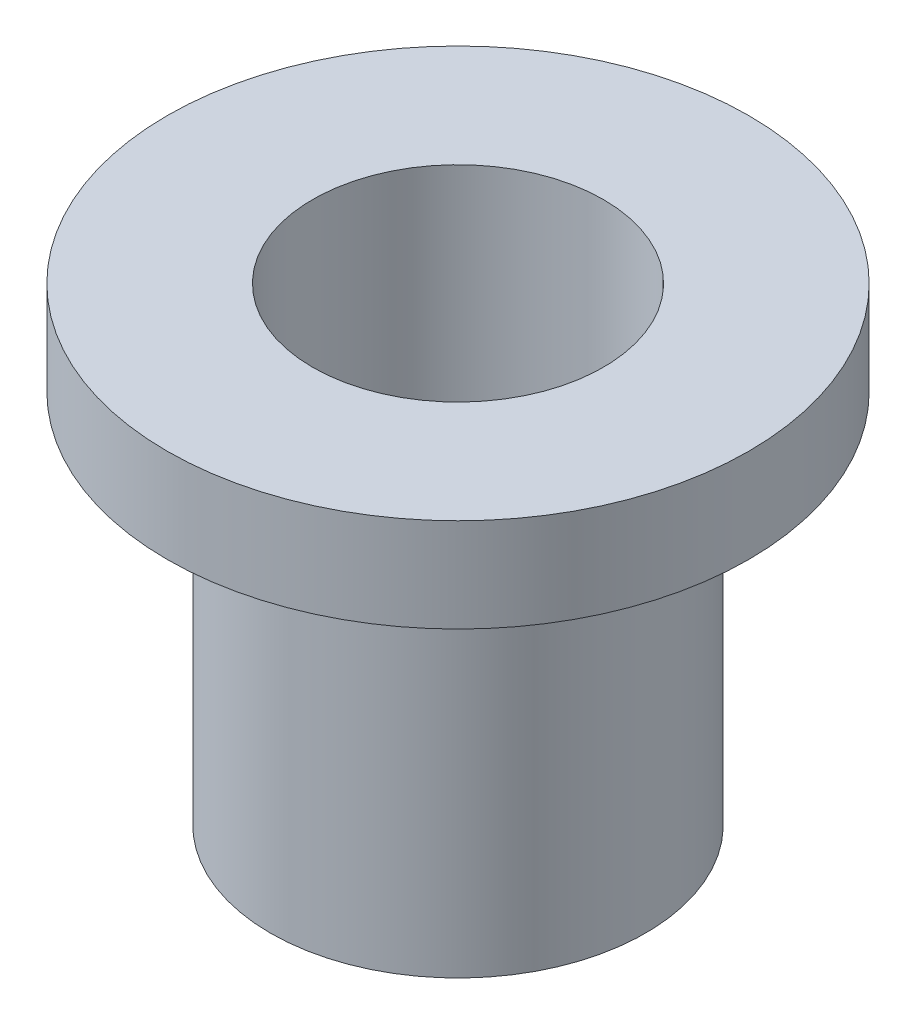
SolidWorks part; units mm, degrees
material "Nylon 101"
ref_plane "Front Plane" through (0, 0, 0) normal (0, 0, 1) x (1, 0, 0)
ref_plane "Top Plane" through (0, 0, 0) normal (0, 1, 0) x (1, 0, 0)
ref_plane "Right Plane" through (0, 0, 0) normal (1, 0, 0) x (0, 0, -1)
sketch "Sketch1" plane through (0, 0, 0) normal (1, 0, 0) x (0, 0, -1)
  line L0 (0, 8.7617) -> (0, -8.7617) construction
  line L1 (1.55, 2.5) -> (3.1, 2.5)
  line L2 (3.1, 2.5) -> (3.1, 1.5)
  line L3 (3.1, 1.5) -> (2, 1.5)
  line L4 (2, 1.5) -> (2, -2.5)
  line L5 (2, -2.5) -> (1.55, -2.5)
  line L6 (1.55, -2.5) -> (1.55, 2.5)
  line L7 (0, 0) -> (1.55, 0) construction
  dimension "D1" = 3.1
  dimension "D2" = 2
  dimension "D3" = 5
  dimension "D4" = 1
  dimension "D5" = 1.55
revolve "Revolve1" add sketch "Sketch1" angle 360 about L0
